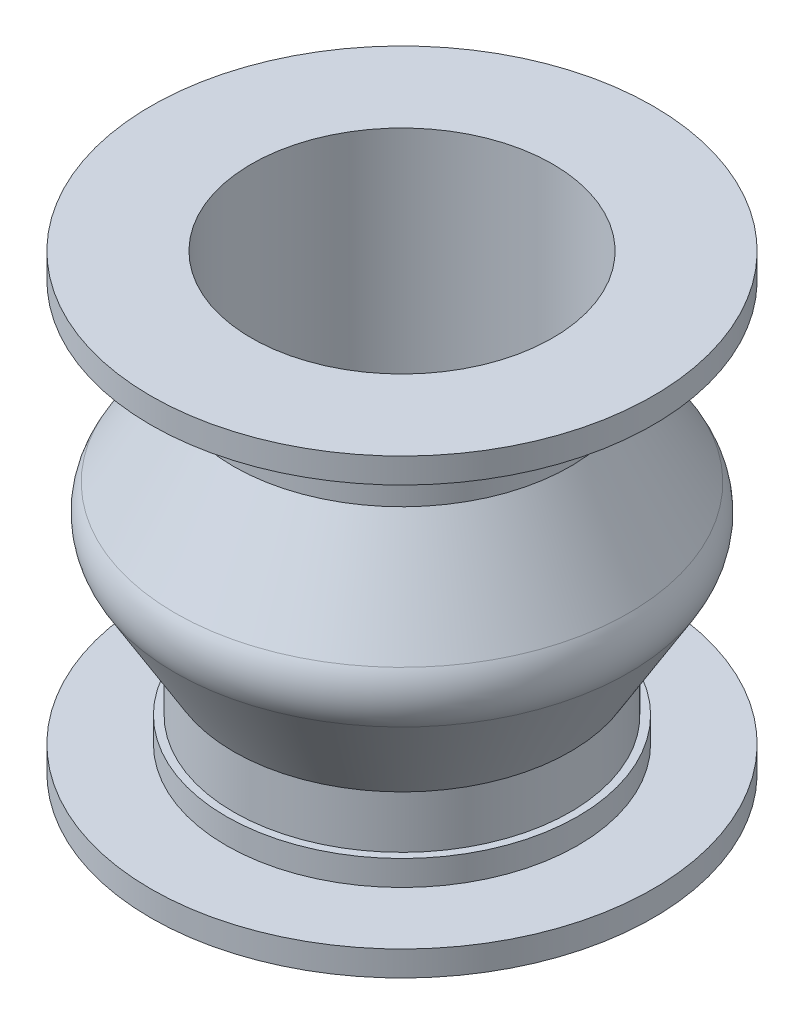
SolidWorks part; units mm, degrees
ref_plane "Front Plane" through (0, 0, 0) normal (0, 0, 1) x (1, 0, 0)
ref_plane "Top Plane" through (0, 0, 0) normal (0, 1, 0) x (1, 0, 0)
ref_plane "Right Plane" through (0, 0, 0) normal (1, 0, 0) x (0, 0, -1)
sketch "Sketch1" plane through (0, 0, 0) normal (0, 0, 1) x (1, 0, 0)
  line L0 (0, 78.9326) -> (0, -67.9775) construction
  line L1 (-88.764, 0) -> (65.7303, 0) construction
  line L2 (0, 45) -> (-50, 45)
  line L3 (-50, 45) -> (-50, 40)
  line L4 (-50, 40) -> (-35, 40)
  line L5 (-33.5, 24.5845) -> (-48.7138, -0.7717) construction
  line L6 (-35, 35) -> (-33.5, 35)
  line L7 (-33.5, -24.5845) -> (-45.1637, -5.145)
  line L8 (-33.5, 35) -> (-33.5, 24.5845)
  line L9 (-35, 40) -> (-35, 35)
  line L10 (-35, 40) -> (-35, 25) construction
  line L11 (-33.5, 24.5845) -> (-45.1637, 5.145)
  line L12 (-35, 25) -> (-50, 0) construction
  line L13 (-33.5, 40) -> (-33.5, 24.5845) construction
  line L14 (-35, -40) -> (-35, -35)
  line L15 (-33.5, -35) -> (-33.5, -24.5845)
  line L16 (-35, -35) -> (-33.5, -35)
  line L17 (-50, -40) -> (-35, -40)
  line L18 (-50, -45) -> (-50, -40)
  line L19 (0, -45) -> (-50, -45)
  line L20 (0, 45) -> (0, -45)
  arc A0 (-45.1637, -5.145) -> (-45.1637, 5.145) centre (-36.5888, 0) cw
  point P10 (-48.2277, 0)
  point P13 (-50, 42.5)
  point P28 (-48.2507, 0)
  dimension "D8" = 10
  dimension "D1" = 50
  dimension "D2" = 24.5845
  dimension "D3" = 48.2507
  dimension "D4" = 35
  dimension "D5" = 45
  dimension "D6" = 40
  dimension "D7" = 35
  dimension "D10" = 1.5
revolve "Revolve1" add sketch "Sketch1" angle 360 about L0
ref_plane "Plane1" through (0, 35, 0) normal (0, 1, 0) x (1, 0, 0)
sketch "Sketch2" plane through (0, 35, 0) normal (0, 1, 0) x (1, 0, 0)
  line L0 (0, 52.073) -> (0, -56.7416) construction
  line L1 (-55.0886, 0) -> (70.6829, 0) construction
  line L2 (-5, 36.6606) -> (-5, 34.641)
  line L3 (5, 36.6606) -> (5, 34.641)
  arc A0 (5, 34.641) -> (-5, 34.641) centre (0, 0) ccw
  arc A1 (5, 36.6606) -> (-5, 36.6606) centre (0, 0) ccw
  circle A3 centre (0, 0) radius 35 construction
  circle A4 centre (0, 0) radius 37 construction
  point P1 (37, 0)
  point P10 (33.4707, 10.233)
  dimension "D1" = 70
  dimension "D3" = 5
  dimension "D2" = 2
extrude "Boss-Extrude1" add sketch "Sketch2" along normal blind 5
sketch "Sketch4" plane through (0, -45, 0) normal (0, -1, 0) x (1, 0, 0)
  circle A0 centre (0, 0) radius 30
  dimension "D1" = 60
extrude "Cut-Extrude1" cut sketch "Sketch4" against normal through all
